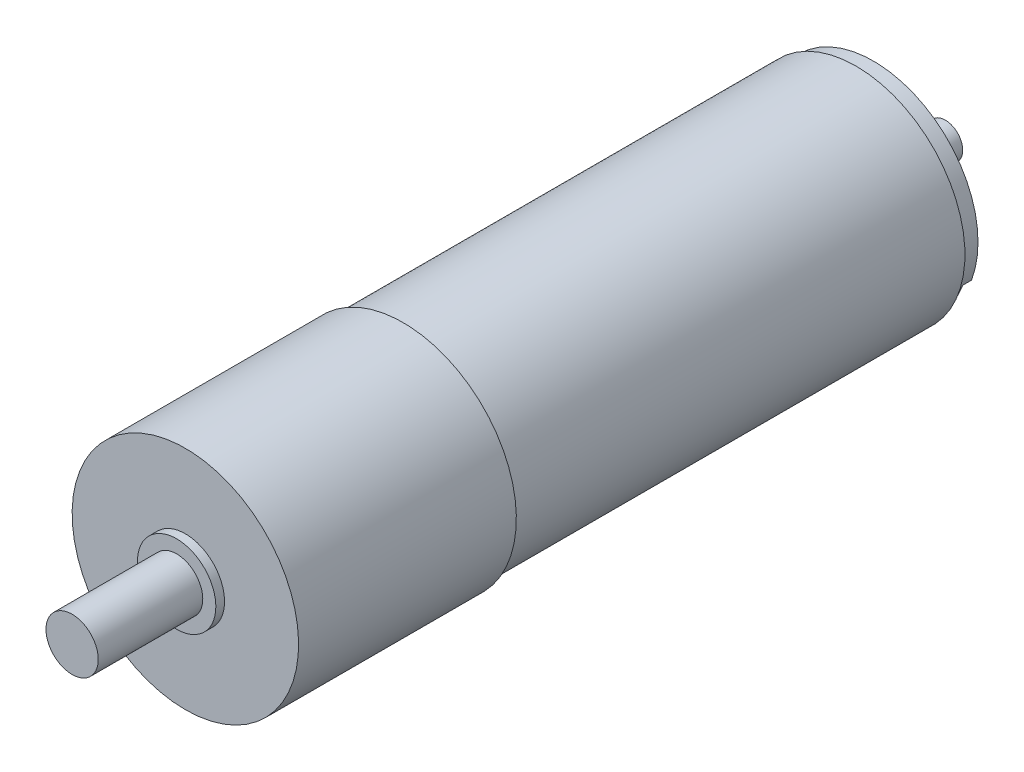
SolidWorks part; units mm, degrees
ref_plane "Front Plane" through (0, 0, 0) normal (0, 0, 1) x (1, 0, 0)
ref_plane "Top Plane" through (0, 0, 0) normal (0, 1, 0) x (1, 0, 0)
ref_plane "Right Plane" through (0, 0, 0) normal (1, 0, 0) x (0, 0, -1)
sketch "Sketch1" plane through (0, 0, 0) normal (1, 0, 0) x (0, 0, -1)
  line L0 (-76, 0) -> (124.5, 0)
  line L1 (-76, 0) -> (-76, 6)
  line L2 (-76, 6) -> (-52, 6)
  line L3 (-52, 6) -> (-52, 9)
  line L4 (-52, 9) -> (-50, 9)
  line L5 (-50, 9) -> (-50, 26)
  line L6 (-50, 26) -> (0, 26)
  line L7 (0, 26) -> (0, 25)
  line L8 (0, 25) -> (104, 25)
  line L10 (108, 8) -> (109, 8)
  line L12 (109, 8) -> (109, 4)
  line L13 (109, 4) -> (124.5, 4)
  line L14 (124.5, 4) -> (124.5, 0)
  line L15 (0, 0) -> (0, 25) construction
  line L16 (104, 25) -> (104, 24)
  line L17 (104, 24) -> (108, 24)
  line L18 (108, 24) -> (108, 8)
  dimension "D1" = 4
  dimension "D2" = 25
  dimension "D3" = 8
  dimension "D4" = 24
  dimension "D5" = 26
  dimension "D6" = 9
  dimension "D7" = 6
  dimension "D8" = 15.5
  dimension "D9" = 1
  dimension "D10" = 4
  dimension "D11" = 104
  dimension "D12" = 50
  dimension "D13" = 2
  dimension "D14" = 24
revolve "Revolve1" add sketch "Sketch1" angle 360 about L0
sketch "Sketch3" plane through (0, 0, -108) normal (0, 0, 1) x (1, 0, 0)
  line L0 (0, 0) -> (-17.1467, 2.9579) construction
  line L1 (-17.1467, 2.9579) -> (-19.906, 3.4339) construction
  line L2 (-19.906, 3.4339) -> (-22.6652, 3.9099) construction
  line L3 (-22.6652, 3.9099) -> (-23.6507, 4.0799) construction
  line L4 (0, 0) -> (5.8297, 16.3943) construction
  line L5 (5.8297, 16.3943) -> (6.7679, 19.0325) construction
  line L6 (6.7679, 19.0325) -> (7.706, 21.6707) construction
  line L7 (7.706, 21.6707) -> (8.041, 22.6129) construction
  line L8 (0, 0) -> (0, -17.4) construction
  line L9 (0, -17.4) -> (0, -20.2) construction
  line L10 (0, -20.2) -> (0, -23) construction
  line L11 (0, -23) -> (0, -24) construction
  line L12 (6.7679, 19.0325) -> (4.3508, 17.619) construction
  line L13 (4.3508, 17.619) -> (-17.4889, 4.8474) construction
  line L14 (-17.4889, 4.8474) -> (-19.906, 3.4339) construction
  line L15 (0, -20.2) -> (-1.8038, -18.0584) construction
  line L16 (-1.8038, -18.0584) -> (-18.1022, 1.2923) construction
  line L17 (-18.1022, 1.2923) -> (-19.906, 3.4339) construction
  circle A0 centre (6.7679, 19.0325) radius 2.8
  circle A1 centre (-19.906, 3.4339) radius 2.8
  circle A2 centre (0, -20.2) radius 2.8
  circle A3 centre (0, 0) radius 24 construction
  point P9 (0, 0)
  point P12 (0, 0)
  point P13 (0, -26.1873)
  point P18 (0, 0)
  point P20 (0, 0)
  point P26 (0, 0)
  point P27 (0, 0)
  point P30 (0, 0)
  point P31 (-23.7401, 3.8248)
  point P32 (8.8615, 19.8205)
  point P33 (0, 0)
  point P34 (-22.7963, 4.9038)
  point P35 (0, 0)
  dimension "D1" = 5.6
  dimension "D2" = 1
  dimension "D3" = 25.3
  dimension "D4" = 25.3
extrude "Cut-Extrude2" cut sketch "Sketch3" along normal blind 3.25
sketch "Sketch4" plane through (0, 0, -108) normal (0, 0, -1) x (-1, 0, 0)
  line L0 (-22.5064, -8.3343) -> (-16.9733, -2.8119)
  line L1 (-16.9733, -2.8119) -> (-2.8449, -16.9678)
  line L2 (-2.8449, -16.9678) -> (-8.3781, -22.4902)
  line L3 (-8.3781, -22.4902) -> (-11.3385, -25.4448)
  line L4 (-11.3385, -25.4448) -> (-25.4668, -11.2889)
  line L5 (-25.4668, -11.2889) -> (-22.5064, -8.3343)
  line L6 (-9.9091, -9.8899) -> (16.9871, 16.954) construction
  line L7 (-9.9091, -9.8899) -> (0, -20.2) construction
  circle A0 centre (0, 0) radius 24 construction
  circle A1 centre (0, 0) radius 26 construction
  circle A2 centre (0, 0) radius 24 construction
  dimension "D1" = 38
  dimension "D2" = 20
  dimension "D3" = 14.3
extrude "Cut-Extrude3" cut sketch "Sketch4" against normal blind 2
